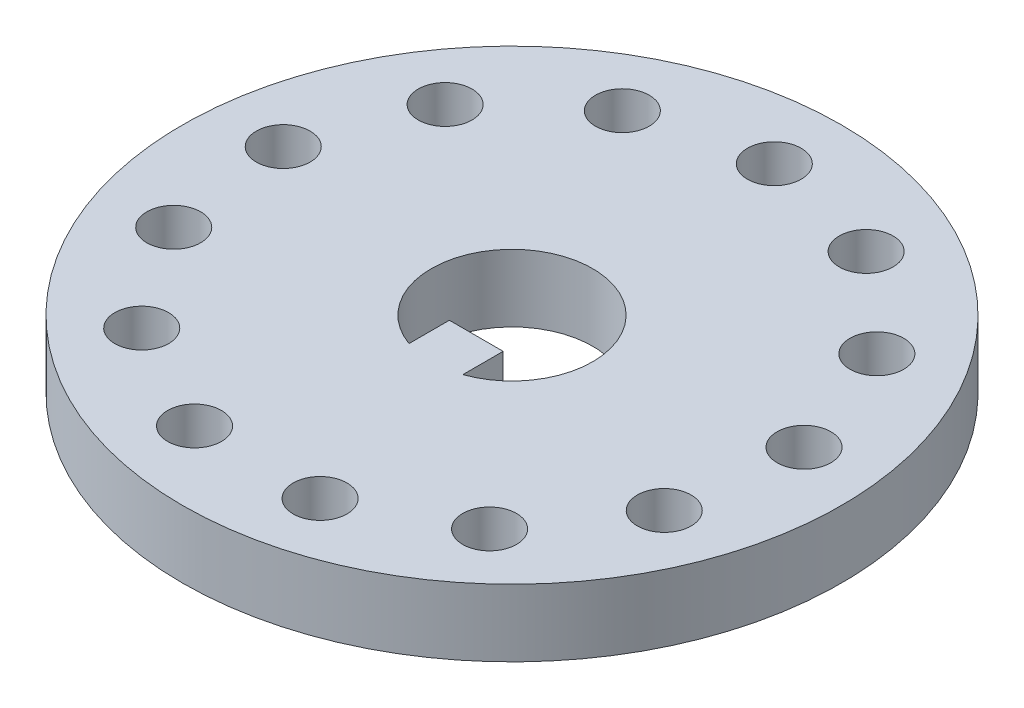
SolidWorks part; units mm, degrees
ref_plane "Front Plane" through (0, 0, 0) normal (0, 0, 1) x (1, 0, 0)
ref_plane "Top Plane" through (0, 0, 0) normal (0, 1, 0) x (1, 0, 0)
ref_plane "Right Plane" through (0, 0, 0) normal (1, 0, 0) x (0, 0, -1)
sketch "Sketch1" plane through (0, 0, 0) normal (0, 1, 0) x (1, 0, 0)
  line L0 (0, 0) -> (0, 26.1271) construction
  line L1 (0, 0) -> (0, 19.5) construction
  line L2 (2, -5.6569) -> (2, -2.6569)
  line L3 (2, -2.6569) -> (-2, -2.6569)
  line L4 (-2, -2.6569) -> (-2, -5.6569)
  circle A0 centre (0, 0) radius 24.5
  arc A1 (2, -5.6569) -> (-2, -5.6569) centre (0, 0) ccw
  circle A2 centre (0, 19.5) radius 2
  circle A3 centre (9.0621, 17.2664) radius 2
  circle A4 centre (16.0482, 11.0773) radius 2
  circle A5 centre (19.3578, 2.3505) radius 2
  circle A6 centre (18.2328, -6.9148) radius 2
  circle A7 centre (12.9309, -14.596) radius 2
  circle A8 centre (4.6667, -18.9334) radius 2
  circle A9 centre (-4.6667, -18.9334) radius 2
  circle A10 centre (-12.9309, -14.596) radius 2
  circle A11 centre (-18.2328, -6.9148) radius 2
  circle A12 centre (-19.3578, 2.3505) radius 2
  circle A13 centre (-16.0482, 11.0773) radius 2
  circle A14 centre (-9.0621, 17.2664) radius 2
  point P7 (0, 24.5)
  dimension "D1" = 49
  dimension "shaft_diameter" = 12
  dimension "D4" = 4
  dimension "D3" = 5
  dimension "D6" = 19.5
  dimension "D2" = 3
  dimension "D7" = 4
  dimension "D5" = 13
extrude "Boss-Extrude1" add sketch "Sketch1" along normal blind 5
equation "\"shaft_diameter\"= 12"
equation "\"outerdiameter\"= 49"
equation "\"numberofbars\"= 13"
equation "\"t\"= 5"
equation "\"width\"=1.5"
equation "\"bardiameter\"=4"
equation "\"D1@Sketch1\" = \"outerdiameter\""
equation "\"D3@Sketch1\"= \"centerdepth\""
equation "\"D4@Sketch1\" = \"bardiameter\""
equation "\"centerdepth\"= 5"
equation "\"D5@Sketch1\" = \"numberofbars\""
equation "\"D1@Boss-Extrude1\"= \"t\""
equation "\"shaft_diameter@Sketch1\"= \"shaft_diameter\""
